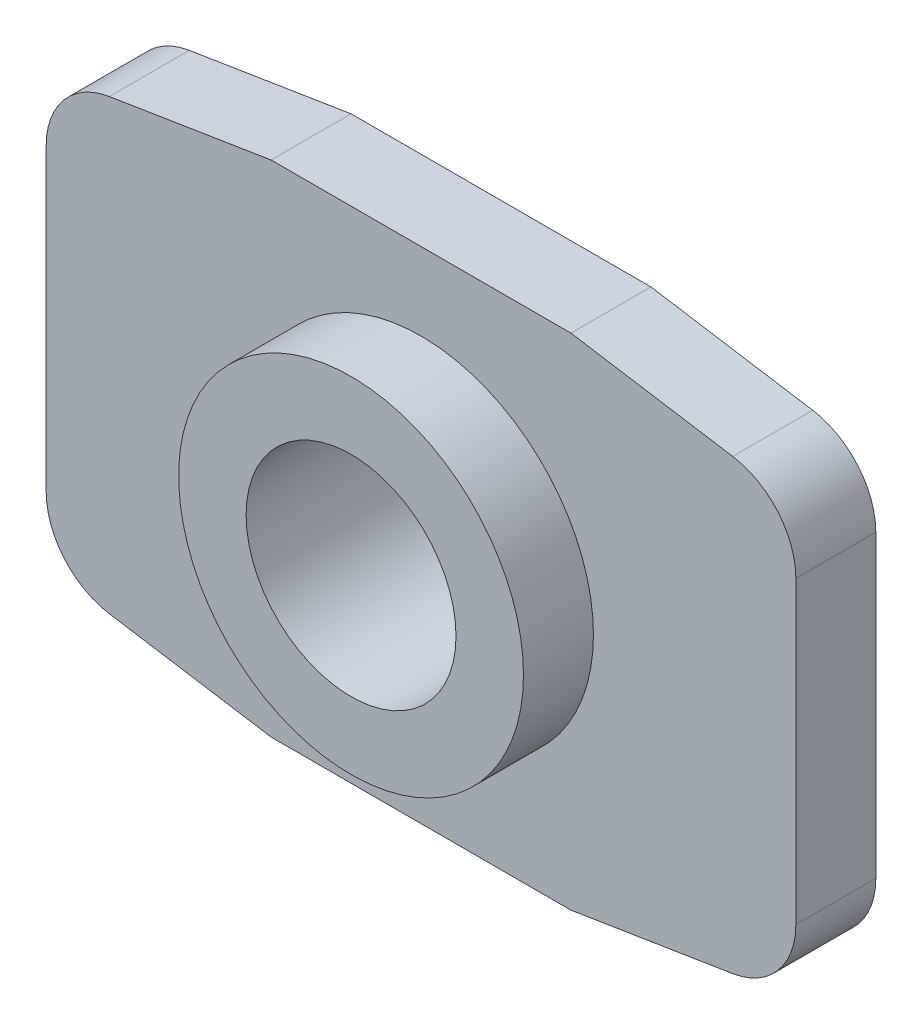
SolidWorks part; units mm, degrees
material "STAINLESS STEEL, 304"
ref_plane "Front Plane" through (0, 0, 0) normal (0, 0, 1) x (1, 0, 0)
ref_plane "Top Plane" through (0, 0, 0) normal (0, 1, 0) x (1, 0, 0)
ref_plane "Right Plane" through (0, 0, 0) normal (1, 0, 0) x (0, 0, -1)
sketch "Sketch1" plane through (0, 0, 0) normal (0, 0, 1) x (1, 0, 0)
  line L0 (-6, -3) -> (6, 3) construction
  line L1 (0, 5) -> (0, -5) construction
  line L2 (-7.5, 0) -> (7.5, 0) construction
  line L16 (7.5, -3) -> (7.5, 3)
  line L17 (3, -5) -> (6.2374, -4.4811)
  line L18 (-3, -5) -> (3, -5)
  line L19 (-6.2374, -4.4811) -> (-3, -5)
  line L20 (-7.5, 3) -> (-7.5, -3)
  line L21 (-3, 5) -> (-6.2374, 4.4811)
  line L22 (3, 5) -> (-3, 5)
  line L23 (6.2374, 4.4811) -> (3, 5)
  arc A8 (6.2374, -4.4811) -> (7.5, -3) centre (6, -3) ccw
  arc A9 (-7.5, -3) -> (-6.2374, -4.4811) centre (-6, -3) ccw
  arc A10 (-6.2374, 4.4811) -> (-7.5, 3) centre (-6, 3) ccw
  arc A11 (7.5, 3) -> (6.2374, 4.4811) centre (6, 3) ccw
  point P3 (0, 0)
  dimension "D1" = 1.5
  dimension "D4" = 6
  dimension "D2" = 10
  dimension "D3" = 15
  dimension "D5" = 6
extrude "Boss-Extrude1" add sketch "Sketch1" along normal blind 1.6 separate body
sketch "Sketch2" plane through (0, 0, 1.6) normal (0, 0, 1) x (1, 0, 0)
  circle A0 centre (0, 0) radius 3.45
  circle A1 centre (0, 0) radius 2.1 construction
  dimension "D1" = 1.35
  dimension "D2" = 4.2
extrude "Boss-Extrude2" add sketch "Sketch2" along normal blind 1.4
hole_wizard " Tapped Hole1" positions "Sketch3" profile "Sketch4" tap size "M5" standard "ISO" end condition up to next
sketch "Sketch3" plane through (0, 0, 0) normal (0, 0, -1) x (-1, 0, 0)
  point P0 (0, 0)
sketch "Sketch4" plane through (0, 0, 0) normal (1, 0, 0) x (0, 1, 0)
  line L0 (0, 0) -> (0, 3)
  line L1 (0, 3) -> (2.1, 3)
  line L2 (2.1, 3) -> (2.1, 0)
  line L5 (2.1, 0) -> (0, 0)
  line L11 (0, -6.35) -> (0, 107.95) construction
  dimension "Thru Tap Drill Dia." = 4.2
  dimension "Thru Tap Drill Depth" = 3
cosmetic thread "Hole Thread1" parameters "D2"=4.4
